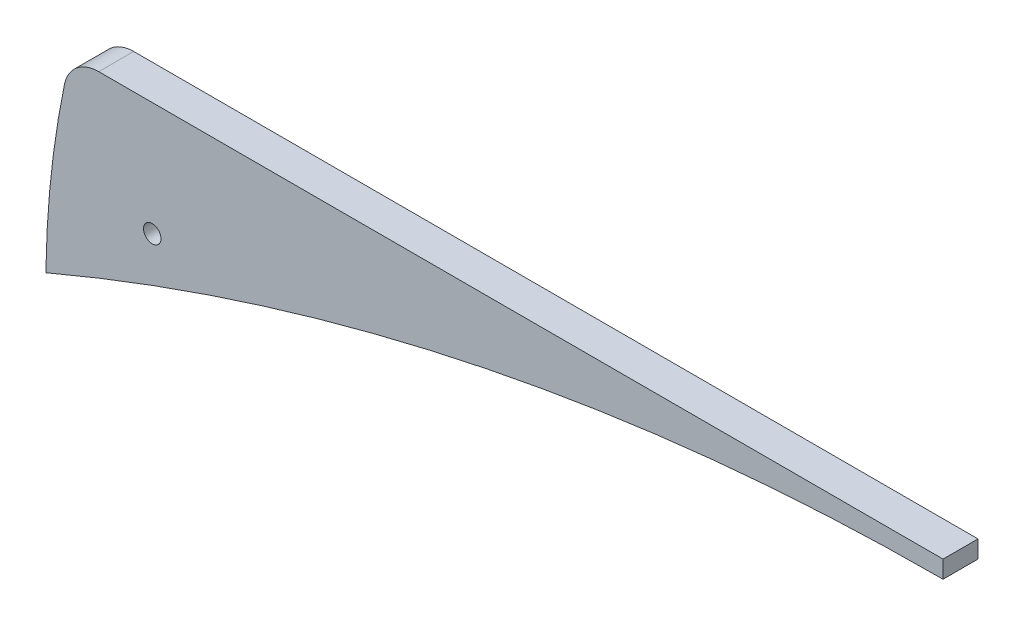
SolidWorks part; units mm, degrees
ref_plane "Přední rovina" through (0, 0, 0) normal (0, 0, 1) x (1, 0, 0)
ref_plane "Horní rovina" through (0, 0, 0) normal (0, 1, 0) x (1, 0, 0)
ref_plane "Pravá rovina" through (0, 0, 0) normal (1, 0, 0) x (0, 0, -1)
sketch "Skica1" plane through (0, 0, 0) normal (0, 0, 1) x (1, 0, 0)
  line L2 (0, 11) -> (0, 12)
  line L3 (0, 12) -> (-48.3078, 12)
  arc A2 (-48.3078, 12) -> (-50.2663, 10.4054) centre (-48.3078, 10) ccw
  arc A3 (-50.2663, 10.4054) -> (-51.3262, 0.7691) centre (0, 0) ccw
  arc A5 (-51.3262, 0.7691) -> (-51.3156, 0.531) centre (-49.3265, 0.7391) ccw
  circle A7 centre (-45.2466, 5.5) radius 0.5
  arc A10 (0, 11) -> (-51.3156, 0.531) centre (0, -120) ccw
extrude "Přidat vysunutím1" add sketch "Skica1" along normal blind 2
